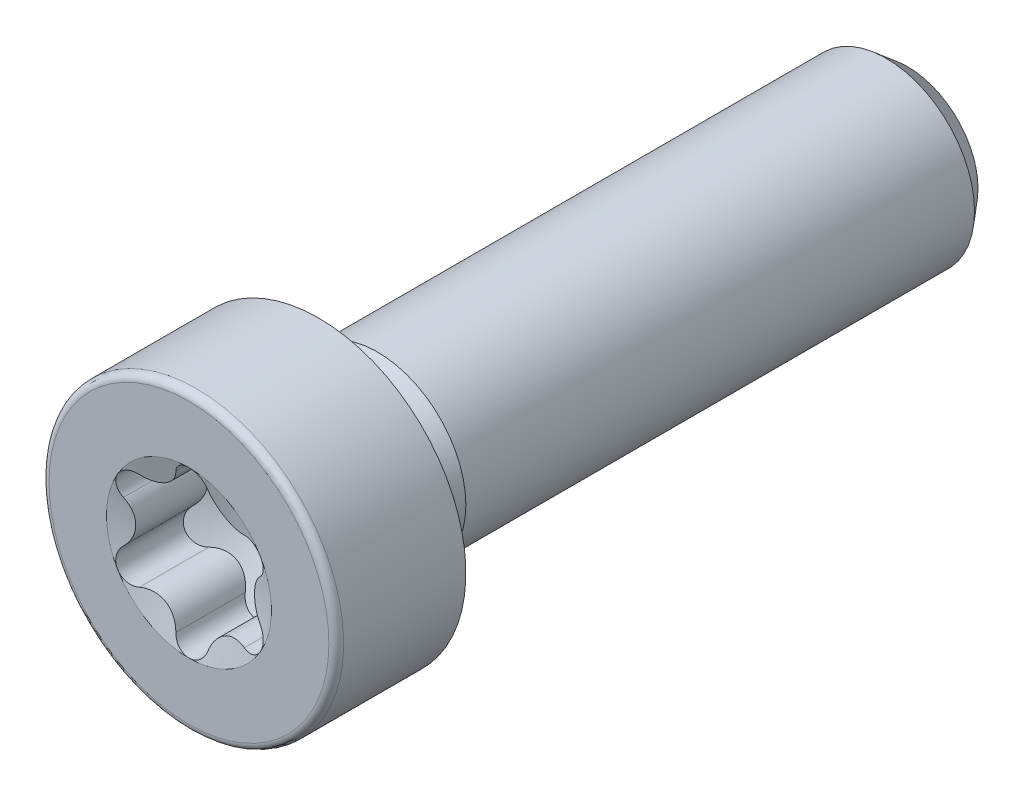
SolidWorks part; units mm, degrees
material "Plain Carbon Steel"
ref_plane "Front Plane" through (0, 0, 0) normal (0, 0, 1) x (1, 0, 0)
ref_plane "Top Plane" through (0, 0, 0) normal (0, 1, 0) x (1, 0, 0)
ref_plane "Right Plane" through (0, 0, 0) normal (1, 0, 0) x (0, 0, -1)
sketch "head-sketch" plane through (0, 0, 0) normal (1, 0, 0) x (0, 0, -1)
  line L0 (0, 0) -> (-4.4, 0) construction
  line L1 (0, 0) -> (0, 5)
  line L2 (0, 5) -> (-4.15, 5)
  line L3 (-4.4, 2.8) -> (-4.4, 0) construction
  line L4 (-4.4, 2.8) -> (-4.1899, 2.016)
  line L5 (-4.1899, 2.016) -> (-4.1899, 0)
  line L6 (-4.1899, 0) -> (0, 0)
  line L7 (-4.4, 2.8) -> (-4.4, 4.75)
  arc A1 (-4.4, 4.75) -> (-4.15, 5) centre (-4.15, 4.75) cw
  dimension "r" = 0.25
  dimension "dk" = 10
  dimension "D2" = 15
  dimension "k" = 4.4
  dimension "A-ref" = 5.6
  dimension "B-ref" = 4.032
ref_plane "6-lobe-plane" through (0, 0, 4.4) normal (0, 0, 1) x (1, 0, 0)
sketch "6-lobe-sketch" plane through (0, 0, 4.4) normal (0, 0, 1) x (1, 0, 0)
  line L0 (0, 0) -> (0, 2.8) construction
  line L1 (0, 0) -> (1.008, 1.7459) construction
  line L2 (1.008, 1.7459) -> (1.498, 2.5946) construction
  line L3 (0, 0) -> (2.4249, 1.4) construction
  line L4 (0, 0) -> (2.4249, -1.4) construction
  line L5 (0, 0) -> (2.996, 0) construction
  line L6 (0, 0) -> (0, -2.8) construction
  line L7 (0, 0) -> (1.498, -2.5946) construction
  line L8 (0, 0) -> (-2.996, 0) construction
  line L9 (0, 0) -> (-1.498, 2.5946) construction
  line L10 (0, 0) -> (-1.498, -2.5946) construction
  line L11 (0, 0) -> (-2.4249, -1.4) construction
  line L12 (0, 0) -> (-2.4249, 1.4) construction
  arc A17 (0.5442, 2.3693) -> (-0.5442, 2.3693) centre (0, 2.2408) ccw
  arc A18 (0.5442, 2.3693) -> (1.7798, 1.656) centre (1.498, 2.5946) ccw
  arc A19 (2.324, 0.7133) -> (1.7798, 1.656) centre (1.9406, 1.1204) ccw
  arc A20 (2.324, 0.7133) -> (2.324, -0.7133) centre (2.996, 0) ccw
  arc A21 (-0.5442, -2.3693) -> (0.5442, -2.3693) centre (0, -2.2408) ccw
  arc A22 (1.7798, -1.656) -> (2.324, -0.7133) centre (1.9406, -1.1204) ccw
  arc A23 (1.7798, -1.656) -> (0.5442, -2.3693) centre (1.498, -2.5946) ccw
  arc A24 (-1.7798, 1.656) -> (-2.324, 0.7133) centre (-1.9406, 1.1204) ccw
  arc A25 (-2.324, -0.7133) -> (-1.7798, -1.656) centre (-1.9406, -1.1204) ccw
  arc A26 (-0.5442, -2.3693) -> (-1.7798, -1.656) centre (-1.498, -2.5946) ccw
  arc A27 (-2.324, -0.7133) -> (-2.324, 0.7133) centre (-2.996, 0) ccw
  arc A28 (-1.7798, 1.656) -> (-0.5442, 2.3693) centre (-1.498, 2.5946) ccw
  arc A29 (-0.5442, 2.3693) -> (-1.7798, 1.656) centre (-1.498, 2.5946) ccw construction
  arc A30 (-1.4563, 0.8408) -> (-1.7798, 1.656) centre (-1.9406, 1.1204) ccw construction
  arc A31 (-2.324, 0.7133) -> (-1.4563, 0.8408) centre (-1.9406, 1.1204) ccw construction
  arc A32 (-2.324, 0.7133) -> (-2.324, -0.7133) centre (-2.996, 0) ccw construction
  arc A33 (-1.4563, -0.8408) -> (-2.324, -0.7133) centre (-1.9406, -1.1204) ccw construction
  arc A34 (-1.7798, -1.656) -> (-1.4563, -0.8408) centre (-1.9406, -1.1204) ccw construction
  arc A35 (-1.7798, -1.656) -> (-0.5442, -2.3693) centre (-1.498, -2.5946) ccw construction
  arc A36 (0, -1.6816) -> (-0.5442, -2.3693) centre (0, -2.2408) ccw construction
  arc A37 (0.5442, -2.3693) -> (0, -1.6816) centre (0, -2.2408) ccw construction
  arc A38 (0.5442, -2.3693) -> (1.7798, -1.656) centre (1.498, -2.5946) ccw construction
  arc A39 (1.4563, -0.8408) -> (1.7798, -1.656) centre (1.9406, -1.1204) ccw construction
  arc A40 (2.324, -0.7133) -> (1.4563, -0.8408) centre (1.9406, -1.1204) ccw construction
  arc A41 (2.324, -0.7133) -> (2.324, 0.7133) centre (2.996, 0) ccw construction
  arc A42 (1.4563, 0.8408) -> (2.324, 0.7133) centre (1.9406, 1.1204) ccw construction
  arc A43 (1.7798, 1.656) -> (1.4563, 0.8408) centre (1.9406, 1.1204) ccw construction
  arc A44 (1.7798, 1.656) -> (0.5442, 2.3693) centre (1.498, 2.5946) ccw construction
  arc A45 (0, 1.6816) -> (0.5442, 2.3693) centre (0, 2.2408) ccw construction
  arc A46 (-0.5442, 2.3693) -> (0, 1.6816) centre (0, 2.2408) ccw construction
  circle A47 centre (0, 0) radius 2.8 construction
  circle A48 centre (0, 0) radius 2.016 construction
  dimension "D1" = 60
  dimension "C-6-lobe" = 1.96
  dimension "A-6-lobe" = 5.6
  dimension "B-6-lobe" = 4.032
sketch "dia-sketch" plane through (0, 0, 0) normal (0, 0, 1) x (1, 0, 0)
  circle A0 centre (0, 0) radius 3
  dimension "dia" = 6
sketch "length-sketch" plane through (0, 0, 0) normal (1, 0, 0) x (0, 0, -1)
  line L0 (0, 0) -> (20, 0) construction
  dimension "length" = 20
ref_plane "length-end-plane" through (0, 0, -20) normal (0, 0, -1) x (-1, 0, 0)
sketch "pitch-sketch" [suppressed] plane through (0, 0, 0) normal (1, 0, 0) x (0, 0, -1)
  line L0 (0, 0) -> (0.4, 0)
  dimension "pitch" = 1
sketch "thread-sketch" plane through (0, 0, 0) normal (1, 0, 0) x (0, 0, -1)
  line L0 (0, 0) -> (20, 0) construction
  line L1 (0, 0) -> (20, 0) construction
  line L2 (0, 3) -> (2, 3)
  line L3 (2, 3) -> (1, 2.675)
  line L4 (1, 2.675) -> (0, 2.675)
  line L5 (0, 2.675) -> (0, 3)
  line L6 (0, 2.675) -> (0, 0) construction
  dimension "Dia-2" = 6
  dimension "threadtransition" = 1
  dimension "pitch-dia" = 5.35
  dimension "runout" = 2
sketch "chamfer-sketch" plane through (0, 0, 0) normal (1, 0, 0) x (0, 0, -1)
  line L0 (20, 0) -> (20, 2.3865) construction
  line L2 (0, 0) -> (20, 0) construction
  line L3 (0, 0) -> (20, 0) construction
  line L4 (20, 2.3865) -> (20, 3)
  line L5 (20, 3) -> (19.2689, 3)
  line L6 (19.2689, 3) -> (20, 2.3865)
  dimension "minor-dia" = 4.773
  dimension "D1" = 50
  dimension "dia-3" = 6
sketch "fillet-sketch" plane through (0, 0, 0) normal (1, 0, 0) x (0, 0, -1)
  line L0 (0, 0) -> (20, 0) construction
  line L1 (0, 0) -> (20, 0) construction
  line L2 (0, 2.675) -> (1, 2.675)
  line L3 (0, 2.675) -> (0, 3.4)
  line L4 (0, 2.675) -> (0, 0) construction
  line L5 (0.1464, 3.0375) -> (0, 3.0375) construction
  arc A0 (1, 2.675) -> (0.1464, 3.0375) centre (1, 3.8613) cw
  arc A1 (0, 3.4) -> (0.1464, 3.0375) centre (0.522, 3.4) ccw
  dimension "r" = 0.522
  dimension "pitch-fillet" = 1
  dimension "fillet-dia" = 5.35
  dimension "da" = 6.8
sketch "socket-depth-sketch" plane through (0, 0, 0) normal (1, 0, 0) x (0, 0, -1)
  line L0 (-4.4, 0) -> (-2.11, 0) construction
  line L1 (-4.1899, 0) -> (0, 0) construction
  line L2 (-2.11, 0) -> (-0.86, 0) construction
  dimension "t" = 2.29
  dimension "t+" = 1.25
ref_plane "socket-bottom-plane" through (0, 0, 0.86) normal (0, 0, -1) x (-1, 0, 0)
sketch "socket-revolve-sketch" plane through (0, 0, 0) normal (1, 0, 0) x (0, 0, -1)
  line L0 (0, 0) -> (0, 5)
  line L1 (0, 5) -> (-2.11, 5)
  line L2 (0, 5) -> (-4.15, 5) construction
  line L3 (-2.11, 5) -> (-2.11, 2.8)
  line L4 (-2.11, 2.8) -> (-0.86, 0)
  line L5 (-0.86, 0) -> (0, 0)
  line L6 (0, 0) -> (1.1467, 0) construction
  line L7 (-2.11, 2.8) -> (-2.11, 0) construction
  line L8 (-2.11, 2.8) -> (-4.4, 2.8) construction
sketch "mat-dia-sketch" plane through (0, 0, -20) normal (0, 0, -1) x (-1, 0, 0)
  circle A0 centre (0, 0) radius 2.4
  dimension "Dx" = 4.8
sketch "mat-length-sketch" plane through (0, 0, 0) normal (1, 0, 0) x (0, 0, -1)
  line L0 (20, 0) -> (23, 0) construction
  dimension "Z4" = 3
ref_plane "mat-end-plane" through (0, 0, -23) normal (0, 0, -1) x (-1, 0, 0)
sketch "mat-cut" plane through (0, 0, 0) normal (1, 0, 0) x (0, 0, -1)
  line L0 (20, 2.4) -> (20, 3)
  line L1 (20, 3) -> (17.55, 3)
  line L2 (17.55, 3) -> (20, 2.4)
  line L3 (22.25, 2.4) -> (23, 2.4)
  line L4 (23, 2.4) -> (23, 2)
  line L5 (20, 0) -> (20, 2.4) construction
  line L7 (20, 0) -> (23, 0) construction
  line L8 (20, -2.4) -> (20, 2.4) construction
  line L9 (20, 2.4) -> (22.25, 2.4) construction
  line L10 (23, -0.8397) -> (23, 0.8397) construction
  line L11 (23, 2) -> (23, 0) construction
  arc A0 (22.25, 2.4) -> (23, 2) centre (22.25, 1.4969) cw
  dimension "mat-dia" = 6
  dimension "U-ref" = 2.45
  dimension "Z5" = 0.75
  dimension "Dy" = 4
sketch "VSMP-boss" plane through (0, 0, 0) normal (1, 0, 0) x (0, 0, -1)
  line L0 (20, 0) -> (12.1951, 0) construction
  line L1 (20, 0) -> (20.9, 0)
  line L2 (20.9, 0) -> (20.9, 2.15)
  line L3 (20.9, 2.15) -> (20, 2.3865)
  line L4 (20, 2.3865) -> (20, 0)
  dimension "Z4" = 0.9
  dimension "Dt" = 4.3
sketch "VSMP-cut" plane through (0, 0, 0) normal (1, 0, 0) x (0, 0, -1)
  line L0 (20, 0) -> (12.1951, 0) construction
  line L1 (20, 2.3865) -> (20, 3)
  line L2 (20, 3) -> (17.45, 3)
  line L3 (17.45, 3) -> (20, 2.3865)
  dimension "Uref" = 2.55
sketch "SDpoint" plane through (0, 0, 0) normal (1, 0, 0) x (0, 0, -1)
  line L0 (20, 0) -> (9.1343, 0) construction
  line L2 (20, 0) -> (21.5, 0)
  line L3 (21.5, 0) -> (21.5, 2)
  line L4 (21.5, 2) -> (20.3865, 2)
  line L5 (20.3865, 2) -> (20, 2.3865)
  line L6 (20, 2.3865) -> (20, 0)
  dimension "D1" = 45
  dimension "z1" = 1.5
  dimension "dp" = 4
sketch "LDpoint" plane through (0, 0, 0) normal (1, 0, 0) x (0, 0, -1)
  line L0 (20, 0) -> (9.1777, 0) construction
  line L2 (20, 0) -> (23, 0)
  line L3 (23, 0) -> (23, 2)
  line L4 (23, 2) -> (20.3865, 2)
  line L5 (20.3865, 2) -> (20, 2.3865)
  line L6 (20, 2.3865) -> (20, 0)
  dimension "D1" = 45
  dimension "dp" = 4
  dimension "z2" = 3
sketch "PCpoint" plane through (0, 0, 0) normal (1, 0, 0) x (0, 0, -1)
  line L0 (20, 0) -> (12.2128, 0) construction
  line L1 (20, 0) -> (23, 0)
  line L2 (23, 0) -> (23, 0.25)
  line L3 (23, 0.25) -> (21, 2.25)
  line L4 (21, 2.25) -> (20.3066, 2.25)
  line L5 (20, 0) -> (20, 2.3865) construction
  line L6 (20, 2.3865) -> (20.3066, 2.25)
  line L7 (20, 2.3865) -> (18.6843, 3)
  line L8 (18.6843, 3) -> (18.6843, 0)
  line L10 (18.6843, 0) -> (20, 0)
  line L11 (18.6843, 3) -> (20, 3) construction
  dimension "D1" = 25
  dimension "D2" = 24
  dimension "D3" = 45
  dimension "z4" = 3
  dimension "z5" = 2
  dimension "D4" = 1.3157
  dimension "dx" = 4.5
sketch "PCpoint-cut" plane through (0, 0, 0) normal (1, 0, 0) x (0, 0, -1)
  line L5 (20, 2.3865) -> (18.6843, 3) construction
  line L6 (20, 2.3865) -> (18.6843, 3)
  line L7 (18.6843, 3) -> (20, 3)
  line L8 (20, 3) -> (20, 2.3865)
  line L9 (20, 0) -> (18.6843, 0) construction
  dimension "cutlength" = 1.3157
sketch "flat-washer" plane through (0, 0, 0) normal (1, 0, 0) x (0, 0, -1)
  line L0 (0, 0) -> (0, 2.81) construction
  line L1 (0, 0) -> (0, 5) construction
  line L2 (0, 0) -> (0.25, 0) construction
  line L3 (0, 2.81) -> (0.25, 2.81)
  line L4 (0, 2.81) -> (0, 2.5)
  line L5 (0, 2.5) -> (0.25, 2.5)
  line L6 (0.25, 2.81) -> (0.25, 2.5)
  line L7 (0, 0) -> (20, 0) construction
  line L8 (0.25, 0) -> (0.25, 2.81) construction
  dimension "D1" = 0.25
  dimension "D2" = 5
  dimension "ID" = 5.62
sketch "conical-washer" plane through (0, 0, 0) normal (1, 0, 0) x (0, 0, -1)
  line L0 (0, 0) -> (0, 2.81) construction
  line L1 (0, 0) -> (0, 5) construction
  line L2 (0, 2.81) -> (0.5, 2.81) construction
  line L3 (0.5, 2.81) -> (0.5, 2) construction
  line L4 (0.5, 2) -> (0, 2) construction
  line L5 (0, 2) -> (0, 2.81) construction
  line L6 (0.5, 2.81) -> (0.5, 0) construction
  line L7 (0, 0) -> (20, 0) construction
  line L8 (0.5, 0) -> (0, 0) construction
  line L9 (0, 2.81) -> (0.25, 2.81) construction
  line L10 (0, 2.724) -> (0.2347, 2.81)
  line L11 (0.2347, 2.81) -> (0.5, 2.086)
  line L12 (0.5, 2.086) -> (0.2653, 2)
  line L13 (0.2653, 2) -> (0, 2.724)
  dimension "D1" = 0.5
  dimension "D2" = 4
  dimension "D3" = 0.25
sketch "double-washer" plane through (0, 0, 0) normal (1, 0, 0) x (0, 0, -1)
  line L0 (0.2653, 2) -> (0, 2.724) construction
  line L1 (0, 2.724) -> (0.2347, 2.81) construction
  line L2 (0.2347, 2.81) -> (0.5, 2.086) construction
  line L3 (0.5, 2.086) -> (0.2653, 2) construction
  line L4 (0.2653, 2) -> (0, 2.724)
  line L5 (0, 2.724) -> (0.2347, 2.81)
  line L6 (0.2347, 2.81) -> (0.5, 2.086)
  line L7 (0.5, 2.086) -> (0.2653, 2)
  line L8 (0, 2.5) -> (0.25, 2.5) construction
  line L9 (0.5, 2.81) -> (0.75, 2.81)
  line L10 (0.5, 2.81) -> (0.5, 2.5)
  line L11 (0.5, 2.5) -> (0.75, 2.5)
  line L12 (0.75, 2.81) -> (0.75, 2.5)
  line L13 (0, 0) -> (0.75, 0) construction
  line L14 (0, 0) -> (20, 0) construction
  line L15 (0.75, 0) -> (0.75, 2.81) construction
sketch "B" plane through (0, 0, 0) normal (1, 0, 0) x (0, 0, -1)
  line L0 (20, 0) -> (-18, 0) construction
  line L1 (0, 0) -> (20, 0) construction
  dimension "B" = 38
sketch "hA" plane through (0, 0, 0) normal (1, 0, 0) x (0, 0, -1)
  line L0 (0, 0) -> (0.75, 0) construction
  line L1 (0, 0) -> (20, 0) construction
  dimension "hA" = 0.75
sketch "flat-thread-cut" plane through (0, 0, 0) normal (1, 0, 0) x (0, 0, -1)
  line L0 (0, 3) -> (0, 0) construction
  line L1 (0, 0) -> (0, 5) construction
  line L2 (0, 0) -> (0.25, 0) construction
  line L3 (0, 0) -> (20, 0) construction
  line L4 (0.25, 0) -> (0.25, 2.675) construction
  line L5 (0.25, 2.675) -> (1.25, 3)
  line L6 (1.25, 3) -> (0, 3)
  line L7 (0, 3) -> (0, 2.675)
  line L8 (0, 2.675) -> (0.25, 2.675)
  dimension "D1" = 1
  dimension "D2" = 6
  dimension "A" = 0.25
  dimension "D4" = 5.35
sketch "conical-thread-cut" plane through (0, 0, 0) normal (1, 0, 0) x (0, 0, -1)
  line L0 (0, 3) -> (0, 0) construction
  line L2 (0, 0) -> (0.5, 0) construction
  line L4 (0.5, 0) -> (0.5, 2.675) construction
  line L5 (0.5, 2.675) -> (1.5, 3)
  line L6 (1.5, 3) -> (0, 3)
  line L7 (0, 3) -> (0, 2.675)
  line L8 (0, 2.675) -> (0.5, 2.675)
  dimension "D1" = 1
  dimension "D2" = 6
  dimension "D4" = 5.35
  dimension "A" = 0.5
sketch "double-thread-cut" plane through (0, 0, 0) normal (1, 0, 0) x (0, 0, -1)
  line L0 (0, 3) -> (0, 0) construction
  line L2 (0, 0) -> (0.75, 0) construction
  line L4 (0.75, 0) -> (0.75, 2.675) construction
  line L5 (0.75, 2.675) -> (1.75, 3)
  line L6 (1.75, 3) -> (0, 3)
  line L7 (0, 3) -> (0, 2.675)
  line L8 (0, 2.675) -> (0.75, 2.675)
  dimension "D1" = 1
  dimension "D2" = 6
  dimension "D4" = 5.35
  dimension "A" = 0.75
sketch "head-cut" plane through (0, 0, 4.4) normal (0, 0, 1) x (1, 0, 0)
  circle A0 centre (0, 0) radius 5.5
  dimension "OD" = 11
ref_plane "head-cut-end" through (0, 0, 0) normal (0, 0, -1) x (-1, 0, 0)
sketch "low-head" plane through (0, 0, 0) normal (1, 0, 0) x (0, 0, -1)
  line L0 (0, 0) -> (3.5646, 0) construction
  line L1 (0, 0) -> (-1.5, 0)
  line L2 (-1.5, 0) -> (-1.5, 4.5)
  line L3 (-1.5, 4.5) -> (-1, 5)
  line L4 (-1, 5) -> (-0.25, 5)
  line L5 (0, 4.75) -> (0, 0)
  arc A0 (-0.25, 5) -> (0, 4.75) centre (-0.25, 4.75) cw
  dimension "r-low" = 0.25
  dimension "k-low" = 1.5
  dimension "d2" = 10
  dimension "v" = 0.5
  dimension "D3" = 45
sketch "low-socket-depth" plane through (0, 0, 0) normal (1, 0, 0) x (0, 0, -1)
  line L0 (-1.5, 0) -> (0.6, 0) construction
  line L1 (0, 0) -> (-1.5, 0) construction
  line L2 (0.6, 0) -> (1.05, 0) construction
  line L3 (0, 0) -> (3.5646, 0) construction
  dimension "t" = 2.1
  dimension "t+" = 0.45
ref_plane "low-6-lobe" through (0, 0, 1.5) normal (0, 0, 1) x (1, 0, 0)
ref_plane "low-socket-end" through (0, 0, -1.05) normal (0, 0, -1) x (-1, 0, 0)
sketch "small-6-lobe" plane through (0, 0, 1.5) normal (0, 0, 1) x (1, 0, 0)
  line L0 (0, 1.5805) -> (0, -1.5805) construction
  line L1 (1.0566, 1.8301) -> (0, 0) construction
  circle A15 centre (0, 0) radius 1.422 construction
  circle A16 centre (0, 0) radius 1.975 construction
  arc A17 (0.3839, 1.6712) -> (-0.3839, 1.6712) centre (0, 1.5805) ccw
  arc A18 (0.3839, 1.6712) -> (1.2554, 1.1681) centre (1.0566, 1.8301) ccw
  arc A19 (-0.3839, -1.6712) -> (0.3839, -1.6712) centre (0, -1.5805) ccw
  arc A20 (1.6393, 0.5032) -> (1.2554, 1.1681) centre (1.3688, 0.7903) ccw
  arc A21 (1.2554, -1.1681) -> (1.6393, -0.5032) centre (1.3688, -0.7903) ccw
  arc A22 (-1.6393, -0.5032) -> (-1.2554, -1.1681) centre (-1.3688, -0.7903) ccw
  arc A23 (-1.2554, 1.1681) -> (-1.6393, 0.5032) centre (-1.3688, 0.7903) ccw
  arc A24 (1.6393, 0.5032) -> (1.6393, -0.5032) centre (2.1132, 0) ccw
  arc A25 (1.2554, -1.1681) -> (0.3839, -1.6712) centre (1.0566, -1.8301) ccw
  arc A26 (-0.3839, -1.6712) -> (-1.2554, -1.1681) centre (-1.0566, -1.8301) ccw
  arc A27 (-1.6393, -0.5032) -> (-1.6393, 0.5032) centre (-2.1132, 0) ccw
  arc A28 (-1.2554, 1.1681) -> (-0.3839, 1.6712) centre (-1.0566, 1.8301) ccw
  arc A29 (1.4924, 1.2936) -> (0.374, 1.9393) centre (1.0566, 1.8301) ccw construction
  arc A30 (1.8665, -0.6457) -> (1.8665, 0.6457) centre (2.1132, 0) ccw construction
  arc A31 (0.374, -1.9393) -> (1.4924, -1.2936) centre (1.0566, -1.8301) ccw construction
  arc A32 (-1.4924, -1.2936) -> (-0.374, -1.9393) centre (-1.0566, -1.8301) ccw construction
  arc A33 (-1.8665, 0.6457) -> (-1.8665, -0.6457) centre (-2.1132, 0) ccw construction
  arc A34 (-0.374, 1.9393) -> (-1.4924, 1.2936) centre (-1.0566, 1.8301) ccw construction
  arc A35 (-0.3401, 1.3807) -> (0, 1.1861) centre (0, 1.5805) ccw construction
  arc A36 (0, 1.1861) -> (0.3401, 1.3807) centre (0, 1.5805) ccw construction
  arc A37 (1.0257, 0.9849) -> (1.3658, 0.3958) centre (1.3688, 0.7903) ccw construction
  arc A38 (1.3658, -0.3958) -> (1.0257, -0.9849) centre (1.3688, -0.7903) ccw construction
  arc A39 (0.3401, -1.3807) -> (0, -1.1861) centre (0, -1.5805) ccw construction
  arc A40 (0, -1.1861) -> (-0.3401, -1.3807) centre (0, -1.5805) ccw construction
  arc A41 (-1.0257, -0.9849) -> (-1.3658, -0.3958) centre (-1.3688, -0.7903) ccw construction
  arc A42 (-1.3658, 0.3958) -> (-1.0257, 0.9849) centre (-1.3688, 0.7903) ccw construction
  arc A43 (0.374, 1.9393) -> (0.3839, 1.6712) centre (1.0566, 1.8301) ccw construction
  arc A44 (1.2554, 1.1681) -> (1.4924, 1.2936) centre (1.0566, 1.8301) ccw construction
  arc A45 (1.8665, 0.6457) -> (1.6393, 0.5032) centre (2.1132, 0) ccw construction
  arc A46 (1.6393, -0.5032) -> (1.8665, -0.6457) centre (2.1132, 0) ccw construction
  arc A47 (1.4924, -1.2936) -> (1.2554, -1.1681) centre (1.0566, -1.8301) ccw construction
  arc A48 (0.3839, -1.6712) -> (0.374, -1.9393) centre (1.0566, -1.8301) ccw construction
  arc A49 (-0.374, -1.9393) -> (-0.3839, -1.6712) centre (-1.0566, -1.8301) ccw construction
  arc A50 (-1.2554, -1.1681) -> (-1.4924, -1.2936) centre (-1.0566, -1.8301) ccw construction
  arc A51 (-1.8665, -0.6457) -> (-1.6393, -0.5032) centre (-2.1132, 0) ccw construction
  arc A52 (-1.6393, 0.5032) -> (-1.8665, 0.6457) centre (-2.1132, 0) ccw construction
  arc A53 (-1.4924, 1.2936) -> (-1.2554, 1.1681) centre (-1.0566, 1.8301) ccw construction
  arc A54 (-0.3839, 1.6712) -> (-0.374, 1.9393) centre (-1.0566, 1.8301) ccw construction
  arc A55 (0.3401, 1.3807) -> (0.3839, 1.6712) centre (0, 1.5805) ccw construction
  arc A56 (1.2554, 1.1681) -> (1.0257, 0.9849) centre (1.3688, 0.7903) ccw construction
  arc A57 (1.3658, 0.3958) -> (1.6393, 0.5032) centre (1.3688, 0.7903) ccw construction
  arc A58 (1.6393, -0.5032) -> (1.3658, -0.3958) centre (1.3688, -0.7903) ccw construction
  arc A59 (1.0257, -0.9849) -> (1.2554, -1.1681) centre (1.3688, -0.7903) ccw construction
  arc A60 (0.3839, -1.6712) -> (0.3401, -1.3807) centre (0, -1.5805) ccw construction
  arc A61 (-0.3401, -1.3807) -> (-0.3839, -1.6712) centre (0, -1.5805) ccw construction
  arc A62 (-1.2554, -1.1681) -> (-1.0257, -0.9849) centre (-1.3688, -0.7903) ccw construction
  arc A63 (-1.3658, -0.3958) -> (-1.6393, -0.5032) centre (-1.3688, -0.7903) ccw construction
  arc A64 (-1.6393, 0.5032) -> (-1.3658, 0.3958) centre (-1.3688, 0.7903) ccw construction
  arc A65 (-1.0257, 0.9849) -> (-1.2554, 1.1681) centre (-1.3688, 0.7903) ccw construction
  arc A66 (-0.3839, 1.6712) -> (-0.3401, 1.3807) centre (0, 1.5805) ccw construction
  point P2 (0, 0)
  dimension "A" = 3.95
  dimension "B" = 2.844
  dimension "C" = 1.3825
  dimension "D3" = 30
sketch "low-socket-revolve" plane through (0, 0, 0) normal (1, 0, 0) x (0, 0, -1)
  line L0 (0.6, 1.975) -> (1.05, 0)
  line L1 (1.05, 0) -> (1.1, 0)
  line L2 (1.1, 0) -> (1.1, 2.075)
  line L3 (1.1, 2.075) -> (0.6, 2.075)
  line L4 (0.6, 2.075) -> (0.6, 1.975)
  line L5 (0.6, 1.975) -> (-1.5, 1.975) construction
  line L6 (1.05, -0.165) -> (1.05, 0.165) construction
  line L7 (0.6, 1.975) -> (0.6, 0) construction
  line L8 (1.05, 0) -> (0.6, 0) construction
  line L9 (-1.5, 0) -> (-1.5, 4.5) construction
  dimension "D1" = 0.1
  dimension "D2" = 0.05
  dimension "A" = 3.95
sketch "threads" plane through (0, 0, 0) normal (1, 0, 0) x (0, 0, -1)
  line L0 (0, 0) -> (20, 0) construction
  line L1 (0, 0) -> (20, 0) construction
  line L2 (20, 2.3865) -> (2, 2.3865)
  line L3 (20, 2.3865) -> (20, 3)
  line L4 (20, 3) -> (19.2689, 3)
  line L5 (19.2689, 3) -> (20, 2.3865)
  line L8 (19.2689, 3) -> (20, 2.3865) construction
  line L9 (2, 2.3865) -> (1, 2.675)
  line L10 (2, 3) -> (0, 3)
  line L11 (1, 2.675) -> (2, 3)
  line L12 (0, 2.675) -> (1, 2.675)
  line L13 (0, 3) -> (0, 2.675)
  line L15 (1, 2.675) -> (2, 3) construction
  line L18 (20, -2.3865) -> (2, -2.3865)
  line L19 (2, -2.3865) -> (1, -2.675)
  dimension "D1" = 0
  dimension "D2" = 0
sketch "patches-1" plane through (0, 0, 0) normal (0, 1, 0) x (1, 0, 0)
  line L0 (0, 20) -> (0, 18)
  dimension "plane length" = 2
ref_plane "patches-2" through (0, 0, -18) normal (0, 0, -1) x (-1, 0, 0)
sketch "180-patch-1" plane through (0, 0, 0) normal (1, 0, 0) x (0, 0, -1)
  line L0 (0, 0) -> (20, 0) construction
  line L1 (11, 3) -> (11, 0) construction
  line L2 (11, 0) -> (14, 0) construction
  circle A0 centre (14, 3) radius 3
  dimension "D2" = 4
  dimension "D1" = 6
sketch "180-patch-2" plane through (0, 0, 0) normal (0, 1, 0) x (1, 0, 0)
  line L0 (0, 14) -> (4.5, 14) construction
  line L1 (0, 0) -> (0, 14) construction
  line L2 (0, 14) -> (-4.5, 14) construction
  dimension "D1" = 9
ref_plane "180-patch-3" through (4.5, 0, -14) normal (1, 0, 0) x (0, 0, -1)
sketch "180-patch-4" plane through (0, 0, -20) normal (0, 0, -1) x (-1, 0, 0)
  circle A0 centre (0, 0) radius 3.01
  circle A1 centre (0, 0) radius 9
  dimension "D1" = 6.02
  dimension "D2" = 18
ref_plane "180-patch-5" through (0, 0, -11) normal (0, 0, -1) x (-1, 0, 0)
ref_plane "180-patch-6" through (-4.5, 0, -14) normal (-1, 0, 0) x (0, 0, 1)
sketch "360-patch" plane through (0, 0, 0) normal (1, 0, 0) x (0, 0, -1)
  line L0 (0, 0) -> (20, 0) construction
  line L1 (11, 3) -> (17, 3)
  line L2 (11, 3) -> (11, 3.01)
  line L3 (11, 3.01) -> (17, 3.01)
  line L4 (17, 3) -> (17, 3.01)
  line L6 (18, 0) -> (18, 3) construction
  line L7 (18, -1.0038) -> (18, 1.0038) construction
  line L8 (17, 3) -> (18, 3) construction
  dimension "D1" = 6
  dimension "D3" = 6
  dimension "D4" = 0.01
  dimension "D2" = 1
sketch "Sketch8" plane through (0, 0, 0) normal (1, 0, 0) x (0, 0, -1)
  line L0 (0, 0) -> (-4.4, 0) construction
  line L1 (-4.4, 2.8) -> (-4.1899, 2.016) construction
  line L2 (-4.1899, 2.016) -> (-4.1899, 0) construction
  line L3 (-4.1899, 0) -> (0, 0) construction
  line L4 (0, 0) -> (0, 5) construction
  line L5 (0, 5) -> (-4.15, 5) construction
  line L6 (0, 0) -> (-4.4, 0) construction
  line L7 (-4.4, 2.8) -> (-4.1899, 2.016)
  line L8 (-4.1899, 2.016) -> (-4.1899, 0)
  line L9 (-4.1899, 0) -> (0, 0)
  line L10 (0, 0) -> (0, 5)
  line L11 (0, 5) -> (-4.15, 5)
  line L12 (-4.4, 2.8) -> (-4.4, 4.75) construction
  line L13 (-4.4, 2.8) -> (-4.4, 4.75)
  arc A1 (-4.15, 5) -> (-4.4, 4.75) centre (-4.15, 4.75) ccw construction
  arc A2 (-4.15, 5) -> (-4.4, 4.75) centre (-4.15, 4.75) ccw
revolve "Head-Revolve1" add sketch "Sketch8" angle 360 about L6
sketch "Sketch9" plane through (0, 0, 4.4) normal (0, 0, 1) x (1, 0, 0)
  arc A36 (0.5442, 2.3693) -> (1.7798, 1.656) centre (1.498, 2.5946) ccw
  arc A37 (2.324, 0.7133) -> (1.7798, 1.656) centre (1.9406, 1.1204) ccw
  arc A38 (2.324, 0.7133) -> (2.324, -0.7133) centre (2.996, 0) ccw
  arc A39 (1.7798, -1.656) -> (2.324, -0.7133) centre (1.9406, -1.1204) ccw
  arc A40 (1.7798, -1.656) -> (0.5442, -2.3693) centre (1.498, -2.5946) ccw
  arc A41 (-0.5442, -2.3693) -> (0.5442, -2.3693) centre (0, -2.2408) ccw
  arc A42 (-0.5442, -2.3693) -> (-1.7798, -1.656) centre (-1.498, -2.5946) ccw
  arc A43 (-2.324, -0.7133) -> (-1.7798, -1.656) centre (-1.9406, -1.1204) ccw
  arc A44 (-2.324, -0.7133) -> (-2.324, 0.7133) centre (-2.996, 0) ccw
  arc A45 (-1.7798, 1.656) -> (-2.324, 0.7133) centre (-1.9406, 1.1204) ccw
  arc A46 (-1.7798, 1.656) -> (-0.5442, 2.3693) centre (-1.498, 2.5946) ccw
  arc A47 (0.5442, 2.3693) -> (-0.5442, 2.3693) centre (0, 2.2408) ccw
  arc A48 (0.5442, 2.3693) -> (1.7798, 1.656) centre (1.498, 2.5946) ccw
  arc A49 (2.324, 0.7133) -> (1.7798, 1.656) centre (1.9406, 1.1204) ccw
  arc A50 (2.324, 0.7133) -> (2.324, -0.7133) centre (2.996, 0) ccw
  arc A51 (1.7798, -1.656) -> (2.324, -0.7133) centre (1.9406, -1.1204) ccw
  arc A52 (1.7798, -1.656) -> (0.5442, -2.3693) centre (1.498, -2.5946) ccw
  arc A53 (-0.5442, -2.3693) -> (0.5442, -2.3693) centre (0, -2.2408) ccw
  arc A54 (-0.5442, -2.3693) -> (-1.7798, -1.656) centre (-1.498, -2.5946) ccw
  arc A55 (-2.324, -0.7133) -> (-1.7798, -1.656) centre (-1.9406, -1.1204) ccw
  arc A56 (-2.324, -0.7133) -> (-2.324, 0.7133) centre (-2.996, 0) ccw
  arc A57 (-1.7798, 1.656) -> (-2.324, 0.7133) centre (-1.9406, 1.1204) ccw
  arc A58 (-1.7798, 1.656) -> (-0.5442, 2.3693) centre (-1.498, 2.5946) ccw
  arc A59 (0.5442, 2.3693) -> (-0.5442, 2.3693) centre (0, 2.2408) ccw
  dimension "D1" = 0
extrude "socket-Cut-Extrude1" cut sketch "Sketch9" against normal up to surface (3.54 mm away)
sketch "Sketch12" plane through (0, 0, 0) normal (1, 0, 0) x (0, 0, -1)
  line L0 (-2.11, 5) -> (-2.11, 2.8) construction
  line L1 (-2.11, 2.8) -> (-0.86, 0) construction
  line L2 (-0.86, 0) -> (0, 0) construction
  line L3 (0, 0) -> (0, 5) construction
  line L4 (0, 5) -> (-2.11, 5) construction
  line L5 (-2.11, 5) -> (-2.11, 2.8)
  line L6 (-2.11, 2.8) -> (-0.86, 0)
  line L7 (-0.86, 0) -> (0, 0)
  line L8 (0, 0) -> (0, 5)
  line L9 (0, 5) -> (-2.11, 5)
  line L10 (0, 0) -> (1.1467, 0) construction
  line L11 (0, 0) -> (1.1467, 0) construction
revolve "Socket-Revolve2" add sketch "Sketch12" angle 360 about L11
sketch "Sketch13" plane through (0, 0, 0) normal (0, 0, 1) x (1, 0, 0)
  circle A0 centre (0, 0) radius 3 construction
  circle A1 centre (0, 0) radius 3
extrude "Length-Boss-Extrude1" add sketch "Sketch13" against normal up to surface (20 mm away) up to plane "length-end-plane"
sketch "Sketch14" plane through (0, 0, 0) normal (1, 0, 0) x (0, 0, -1)
  line L0 (0, 0) -> (20, 0) construction
  line L1 (0, 3) -> (2, 3) construction
  line L2 (2, 3) -> (1, 2.675) construction
  line L3 (1, 2.675) -> (0, 2.675) construction
  line L4 (0, 2.675) -> (0, 3) construction
  line L5 (0, 0) -> (20, 0) construction
  line L6 (0, 3) -> (2, 3)
  line L7 (2, 3) -> (1, 2.675)
  line L8 (1, 2.675) -> (0, 2.675)
  line L9 (0, 2.675) -> (0, 3)
revolve "Runout-Cut-Revolve1" cut sketch "Sketch14" angle 360 about L5
sketch "Sketch15" plane through (0, 0, 0) normal (1, 0, 0) x (0, 0, -1)
  line L0 (0, 2.675) -> (1, 2.675) construction
  line L1 (0, 2.675) -> (0, 3.4) construction
  line L2 (0, 0) -> (20, 0) construction
  line L3 (0, 2.675) -> (0, 0) construction
  line L4 (0, 2.675) -> (1, 2.675)
  line L5 (0, 2.675) -> (0, 3.4)
  line L6 (0, 0) -> (20, 0) construction
  line L7 (0, 2.675) -> (0, 0)
  arc A0 (0, 3.4) -> (0.1464, 3.0375) centre (0.522, 3.4) ccw construction
  arc A1 (0.1464, 3.0375) -> (1, 2.675) centre (1, 3.8613) ccw construction
  arc A2 (0, 3.4) -> (0.1464, 3.0375) centre (0.522, 3.4) ccw
  arc A3 (0.1464, 3.0375) -> (1, 2.675) centre (1, 3.8613) ccw
revolve "Fillet-Revolve3" add sketch "Sketch15" angle 360 about L6
sketch "Sketch16" plane through (0, 0, 0) normal (1, 0, 0) x (0, 0, -1)
  line L0 (0, 0) -> (20, 0) construction
  line L1 (20, 3) -> (19.2689, 3) construction
  line L2 (19.2689, 3) -> (20, 2.3865) construction
  line L3 (20, 2.3865) -> (20, 3) construction
  line L4 (0, 0) -> (20, 0) construction
  line L5 (20, 3) -> (19.2689, 3)
  line L6 (19.2689, 3) -> (20, 2.3865)
  line L7 (20, 2.3865) -> (20, 3)
revolve "Chamfer-Cut-Revolve2" cut sketch "Sketch16" angle 360 about L4
sketch "Sketch21" plane through (0, 0, -20) normal (0, 0, -1) x (-1, 0, 0)
  circle A0 centre (0, 0) radius 2.4 construction
  circle A1 centre (0, 0) radius 2.4
extrude "matpoint-Boss-Extrude1" [suppressed] add sketch "Sketch21" along normal up to surface (4.8 mm away)
sketch "Sketch22" plane through (0, 0, 0) normal (1, 0, 0) x (0, 0, -1)
  line L0 (20, 0) -> (23, 0) construction
  line L1 (23, 2.4) -> (23, 2) construction
  line L2 (22.25, 2.4) -> (23, 2.4) construction
  line L3 (20, 3) -> (17.55, 3) construction
  line L4 (17.55, 3) -> (20, 2.4) construction
  line L5 (20, 2.4) -> (20, 3) construction
  line L6 (20, 0) -> (23, 0) construction
  line L7 (23, 2.4) -> (23, 2)
  line L8 (22.25, 2.4) -> (23, 2.4)
  line L9 (20, 3) -> (17.55, 3)
  line L10 (17.55, 3) -> (20, 2.4)
  line L11 (20, 2.4) -> (20, 3)
  arc A0 (23, 2) -> (22.25, 2.4) centre (22.25, 1.4969) ccw construction
  arc A1 (23, 2) -> (22.25, 2.4) centre (22.25, 1.4969) ccw
revolve "matpoint-Cut-Revolve1" [suppressed] cut sketch "Sketch22" angle 360 about L6
sketch "Sketch40" plane through (0, 0, 0) normal (1, 0, 0) x (0, 0, -1)
  line L0 (20, 0) -> (12.1951, 0) construction
  line L1 (20.9, 2.15) -> (20, 2.3865) construction
  line L2 (20, 2.3865) -> (20, 0) construction
  line L3 (20, 0) -> (20.9, 0) construction
  line L4 (20.9, 0) -> (20.9, 2.15) construction
  line L5 (20, 0) -> (12.1951, 0) construction
  line L6 (20.9, 2.15) -> (20, 2.3865)
  line L7 (20, 2.3865) -> (20, 0)
  line L8 (20, 0) -> (20.9, 0)
  line L9 (20.9, 0) -> (20.9, 2.15)
revolve "VSMP-revolve" [suppressed] add sketch "Sketch40" angle 360 about L5
sketch "Sketch41" plane through (0, 0, 0) normal (1, 0, 0) x (0, 0, -1)
  line L0 (20, 0) -> (12.1951, 0) construction
  line L1 (20, 3) -> (17.45, 3) construction
  line L2 (17.45, 3) -> (20, 2.3865) construction
  line L3 (20, 2.3865) -> (20, 3) construction
  line L4 (20, 0) -> (12.1951, 0) construction
  line L5 (20, 3) -> (17.45, 3)
  line L6 (17.45, 3) -> (20, 2.3865)
  line L7 (20, 2.3865) -> (20, 3)
revolve "VSMP-Cut-Revolve" [suppressed] cut sketch "Sketch41" angle 360 about L4
sketch "Sketch42" plane through (0, 0, 0) normal (1, 0, 0) x (0, 0, -1)
  line L0 (23, 2) -> (20.3865, 2) construction
  line L1 (20.3865, 2) -> (20, 2.3865) construction
  line L2 (20, 2.3865) -> (20, 0) construction
  line L3 (20, 0) -> (23, 0) construction
  line L4 (23, 0) -> (23, 2) construction
  line L5 (20, 0) -> (9.1777, 0) construction
  line L6 (23, 2) -> (20.3865, 2)
  line L7 (20.3865, 2) -> (20, 2.3865)
  line L8 (20, 2.3865) -> (20, 0)
  line L9 (20, 0) -> (23, 0)
  line L10 (23, 0) -> (23, 2)
  line L11 (20, 0) -> (9.1777, 0) construction
revolve "LD" [suppressed] add sketch "Sketch42" angle 360 about L11
sketch "Sketch43" [suppressed] plane through (0, 0, 0) normal (1, 0, 0) x (0, 0, -1)
  line L0 (10, 0) -> (9.1343, 0) construction
  line L1 (10.5, 0.5) -> (10.2545, 0.5) construction
  line L2 (10.2545, 0.5) -> (10, 0.7545) construction
  line L3 (10, 0.7545) -> (10, 0) construction
  line L4 (10, 0) -> (10.5, 0) construction
  line L5 (10.5, 0) -> (10.5, 0.5) construction
  line L6 (10, 0) -> (9.1343, 0) construction
  line L7 (10.5, 0.5) -> (10.2545, 0.5)
  line L8 (10.2545, 0.5) -> (10, 0.7545)
  line L9 (10, 0.7545) -> (10, 0)
  line L10 (10, 0) -> (10.5, 0)
  line L11 (10.5, 0) -> (10.5, 0.5)
revolve "SD" [suppressed] add sketch "Sketch43" angle 360 about L6
sketch "Sketch44" plane through (0, 0, 0) normal (1, 0, 0) x (0, 0, -1)
  line L0 (21, 2.25) -> (20.3066, 2.25) construction
  line L1 (20, 2.3865) -> (20.3066, 2.25) construction
  line L2 (20, 2.3865) -> (18.6843, 3) construction
  line L3 (18.6843, 3) -> (18.6843, 0) construction
  line L4 (18.6843, 0) -> (20, 0) construction
  line L5 (20, 0) -> (23, 0) construction
  line L6 (23, 0) -> (23, 0.25) construction
  line L7 (23, 0.25) -> (21, 2.25) construction
  line L8 (20, 0) -> (12.2128, 0) construction
  line L9 (20, 0) -> (20, 2.3865) construction
  line L10 (21, 2.25) -> (20.3066, 2.25)
  line L11 (20, 2.3865) -> (20.3066, 2.25)
  line L12 (20, 2.3865) -> (18.6843, 3)
  line L13 (18.6843, 3) -> (18.6843, 0)
  line L14 (18.6843, 0) -> (20, 0)
  line L15 (20, 0) -> (23, 0)
  line L16 (23, 0) -> (23, 0.25)
  line L17 (23, 0.25) -> (21, 2.25)
  line L18 (20, 0) -> (12.2128, 0) construction
  line L19 (20, 0) -> (20, 2.3865)
revolve "PC" [suppressed] add sketch "Sketch44" angle 360 about L18
sketch "Sketch45" plane through (0, 0, 0) normal (1, 0, 0) x (0, 0, -1)
  line L0 (20, 0) -> (18.6843, 0) construction
  line L1 (18.6843, 3) -> (20, 3) construction
  line L2 (20, 3) -> (20, 2.3865) construction
  line L3 (20, 2.3865) -> (18.6843, 3) construction
  line L4 (20, 0) -> (18.6843, 0) construction
  line L5 (18.6843, 3) -> (20, 3)
  line L6 (20, 3) -> (20, 2.3865)
  line L7 (20, 2.3865) -> (18.6843, 3)
revolve "PC-cut" [suppressed] cut sketch "Sketch45" angle 360 about L4
sketch "Sketch46" [suppressed] plane through (0, 0, 0) normal (1, 0, 0) x (0, 0, -1)
  line L0 (0, 0) -> (0.25, 0) construction
  line L1 (0, 0.935) -> (0, 2.5) construction
  line L2 (0, 2.5) -> (0.25, 2.5) construction
  line L3 (0.25, 0.935) -> (0.25, 2.5) construction
  line L4 (0, 0.935) -> (0.25, 0.935) construction
  line L5 (0, 0) -> (0.25, 0) construction
  line L6 (0, 0.935) -> (0, 2.5)
  line L7 (0, 2.5) -> (0.25, 2.5)
  line L8 (0.25, 0.935) -> (0.25, 2.5)
  line L9 (0, 0.935) -> (0.25, 0.935)
revolve "Flat SEMS" [suppressed] add sketch "Sketch46" angle 360 about L5
sketch "Sketch47" [suppressed] plane through (0, 0, 0) normal (1, 0, 0) x (0, 0, -1)
  line L0 (0.2579, 2) -> (0, 0.9973) construction
  line L1 (0, 0.9973) -> (0.2421, 0.935) construction
  line L2 (0.2421, 0.935) -> (0.5, 1.9377) construction
  line L3 (0.5, 1.9377) -> (0.2579, 2) construction
  line L4 (0.5, 0) -> (0, 0) construction
  line L7 (0.2579, 2) -> (0, 0.9973)
  line L8 (0, 0.9973) -> (0.2421, 0.935)
  line L9 (0.2421, 0.935) -> (0.5, 1.9377)
  line L10 (0.5, 1.9377) -> (0.2579, 2)
  line L11 (0.5, 0) -> (0, 0) construction
revolve "Conical SEMS" [suppressed] add sketch "Sketch47" angle 360 about L11
sketch "Sketch48" [suppressed] plane through (0, 0, 0) normal (1, 0, 0) x (0, 0, -1)
  line L0 (0, 0) -> (0.75, 0) construction
  line L1 (0.2421, 0.935) -> (0.5, 1.9377) construction
  line L2 (0.5, 1.9377) -> (0.2579, 2) construction
  line L3 (0.2579, 2) -> (0, 0.9973) construction
  line L4 (0, 0.9973) -> (0.2421, 0.935) construction
  line L5 (0.75, 0.935) -> (0.75, 2.5) construction
  line L6 (0.5, 2.5) -> (0.75, 2.5) construction
  line L7 (0.5, 0.935) -> (0.5, 2.5) construction
  line L8 (0.5, 0.935) -> (0.75, 0.935) construction
  line L9 (0, 0) -> (0.75, 0) construction
  line L10 (0.2421, 0.935) -> (0.5, 1.9377)
  line L11 (0.5, 1.9377) -> (0.2579, 2)
  line L12 (0.2579, 2) -> (0, 0.9973)
  line L13 (0, 0.9973) -> (0.2421, 0.935)
  line L14 (0.75, 0.935) -> (0.75, 2.5)
  line L15 (0.5, 2.5) -> (0.75, 2.5)
  line L16 (0.5, 0.935) -> (0.5, 2.5)
  line L17 (0.5, 0.935) -> (0.75, 0.935)
revolve "Double SEMS" [suppressed] add sketch "Sketch48" angle 360 about L9
sketch "Sketch49" [suppressed] plane through (0, 0, 0) normal (1, 0, 0) x (0, 0, -1)
  line L0 (0.65, 1) -> (0, 1) construction
  line L1 (0, 1) -> (0, 0.87) construction
  line L2 (0, 0.87) -> (0.25, 0.87) construction
  line L3 (0.25, 0.87) -> (0.65, 1) construction
  line L4 (0, 0) -> (0.25, 0) construction
  line L7 (0.65, 1) -> (0, 1)
  line L8 (0, 1) -> (0, 0.87)
  line L9 (0, 0.87) -> (0.25, 0.87)
  line L10 (0.25, 0.87) -> (0.65, 1)
  line L11 (0, 0) -> (0.25, 0) construction
revolve "flat_Cut-Revolve" [suppressed] cut sketch "Sketch49" angle 360 about L11
sketch "Sketch50" [suppressed] plane through (0, 0, 0) normal (1, 0, 0) x (0, 0, -1)
  line L0 (0, 0) -> (0.5, 0) construction
  line L1 (0.9, 1) -> (0, 1) construction
  line L2 (0, 1) -> (0, 0.87) construction
  line L3 (0, 0.87) -> (0.5, 0.87) construction
  line L4 (0.5, 0.87) -> (0.9, 1) construction
  line L5 (0, 0) -> (0.5, 0) construction
  line L6 (0.9, 1) -> (0, 1)
  line L7 (0, 1) -> (0, 0.87)
  line L8 (0, 0.87) -> (0.5, 0.87)
  line L9 (0.5, 0.87) -> (0.9, 1)
revolve "Conical-Cut-Revolve" [suppressed] cut sketch "Sketch50" angle 360 about L5
sketch "Sketch51" [suppressed] plane through (0, 0, 0) normal (1, 0, 0) x (0, 0, -1)
  line L0 (1.15, 1) -> (0, 1) construction
  line L1 (0, 1) -> (0, 0.87) construction
  line L2 (0, 0.87) -> (0.75, 0.87) construction
  line L3 (0.75, 0.87) -> (1.15, 1) construction
  line L4 (0, 0) -> (0.75, 0) construction
  line L7 (1.15, 1) -> (0, 1)
  line L8 (0, 1) -> (0, 0.87)
  line L9 (0, 0.87) -> (0.75, 0.87)
  line L10 (0.75, 0.87) -> (1.15, 1)
  line L11 (0, 0) -> (0.75, 0) construction
revolve "Double-Cut-Revolve" [suppressed] cut sketch "Sketch51" angle 360 about L11
sketch "Sketch59" plane through (0, 0, 4.4) normal (0, 0, 1) x (1, 0, 0)
  circle A0 centre (0, 0) radius 5.5 construction
  circle A1 centre (0, 0) radius 5.5
extrude "head-remove" [suppressed] cut sketch "Sketch59" against normal up to surface (1.55 mm away)
sketch "Sketch60" plane through (0, 0, 0) normal (1, 0, 0) x (0, 0, -1)
  line L0 (0, 0) -> (1.8073, 0) construction
  line L1 (0, 0) -> (20, 0) construction
  line L5 (-1.5, 0) -> (0, 0)
  line L6 (-1.5, 4.5) -> (-1.5, 0)
  line L7 (-1, 5) -> (-1.5, 4.5)
  line L8 (-0.25, 5) -> (-1, 5)
  line L9 (0, 0) -> (0, 4.75)
  line L10 (-1.5, 0) -> (0, 0)
  line L11 (-1.5, 4.5) -> (-1.5, 0)
  line L12 (-1, 5) -> (-1.5, 4.5)
  line L13 (-0.25, 5) -> (-1, 5)
  line L14 (0, 0) -> (0, 4.75)
  arc A1 (0, 4.75) -> (-0.25, 5) centre (-0.25, 4.75) ccw
  arc A2 (0, 4.75) -> (-0.25, 5) centre (-0.25, 4.75) ccw
  dimension "D1" = 0
revolve "low-head-Revolve" [suppressed] add sketch "Sketch60" angle 360 about L0
sketch "Sketch61" plane through (0, 0, 1.5) normal (0, 0, 1) x (1, 0, 0)
  arc A12 (0.3839, 1.6712) -> (-0.3839, 1.6712) centre (0, 1.5805) ccw
  arc A13 (0.3839, 1.6712) -> (-0.3839, 1.6712) centre (0, 1.5805) ccw
  arc A14 (-1.2554, 1.1681) -> (-0.3839, 1.6712) centre (-1.0566, 1.8301) ccw
  arc A15 (-1.2554, 1.1681) -> (-0.3839, 1.6712) centre (-1.0566, 1.8301) ccw
  arc A16 (-1.2554, 1.1681) -> (-1.6393, 0.5032) centre (-1.3688, 0.7903) ccw
  arc A17 (-1.2554, 1.1681) -> (-1.6393, 0.5032) centre (-1.3688, 0.7903) ccw
  arc A18 (-1.6393, -0.5032) -> (-1.6393, 0.5032) centre (-2.1132, 0) ccw
  arc A19 (-1.6393, -0.5032) -> (-1.6393, 0.5032) centre (-2.1132, 0) ccw
  arc A20 (-1.6393, -0.5032) -> (-1.2554, -1.1681) centre (-1.3688, -0.7903) ccw
  arc A21 (-1.6393, -0.5032) -> (-1.2554, -1.1681) centre (-1.3688, -0.7903) ccw
  arc A22 (-0.3839, -1.6712) -> (-1.2554, -1.1681) centre (-1.0566, -1.8301) ccw
  arc A23 (-0.3839, -1.6712) -> (-1.2554, -1.1681) centre (-1.0566, -1.8301) ccw
  arc A36 (-0.3839, -1.6712) -> (0.3839, -1.6712) centre (0, -1.5805) ccw
  arc A37 (-0.3839, -1.6712) -> (0.3839, -1.6712) centre (0, -1.5805) ccw
  arc A38 (1.2554, -1.1681) -> (0.3839, -1.6712) centre (1.0566, -1.8301) ccw
  arc A39 (1.2554, -1.1681) -> (0.3839, -1.6712) centre (1.0566, -1.8301) ccw
  arc A40 (1.2554, -1.1681) -> (1.6393, -0.5032) centre (1.3688, -0.7903) ccw
  arc A41 (1.2554, -1.1681) -> (1.6393, -0.5032) centre (1.3688, -0.7903) ccw
  arc A42 (1.6393, 0.5032) -> (1.6393, -0.5032) centre (2.1132, 0) ccw
  arc A43 (1.6393, 0.5032) -> (1.6393, -0.5032) centre (2.1132, 0) ccw
  arc A44 (1.6393, 0.5032) -> (1.2554, 1.1681) centre (1.3688, 0.7903) ccw
  arc A45 (1.6393, 0.5032) -> (1.2554, 1.1681) centre (1.3688, 0.7903) ccw
  arc A46 (0.3839, 1.6712) -> (1.2554, 1.1681) centre (1.0566, 1.8301) ccw
  arc A47 (0.3839, 1.6712) -> (1.2554, 1.1681) centre (1.0566, 1.8301) ccw
  dimension "D1" = 0
extrude "Small-6-lobe-Cut" [suppressed] cut sketch "Sketch61" against normal up to surface (1.15 mm away)
sketch "Sketch62" plane through (0, 0, 0) normal (1, 0, 0) x (0, 0, -1)
  line L0 (1.05, 0) -> (0.6, 0) construction
  line L5 (0.6, 1.975) -> (1.05, 0)
  line L6 (1.05, 0) -> (1.1, 0)
  line L7 (1.1, 0) -> (1.1, 2.075)
  line L8 (1.1, 2.075) -> (0.6, 2.075)
  line L9 (0.6, 2.075) -> (0.6, 1.975)
  line L10 (0.6, 1.975) -> (1.05, 0)
  line L11 (1.05, 0) -> (1.1, 0)
  line L12 (1.1, 0) -> (1.1, 2.075)
  line L13 (1.1, 2.075) -> (0.6, 2.075)
  line L14 (0.6, 2.075) -> (0.6, 1.975)
  dimension "D1" = 0
revolve "Socket-bottom-Revolve" [suppressed] add sketch "Sketch62" angle 360 about L0
sketch "Sketch66" plane through (0, 0, 0) normal (1, 0, 0) x (0, 0, -1)
  circle A0 centre (14, 3) radius 3 construction
  circle A1 centre (14, 3) radius 3
extrude "180-patch-extrude" [suppressed] add sketch "Sketch66" along normal up to surface and the other way up to surface
sketch "Sketch67" plane through (0, 0, -20) normal (0, 0, -1) x (-1, 0, 0)
  circle A0 centre (0, 0) radius 3.01 construction
  circle A1 centre (0, 0) radius 9 construction
  circle A2 centre (0, 0) radius 3.01
  circle A3 centre (0, 0) radius 9
extrude "180-patch-Cut-Extrude" [suppressed] cut sketch "Sketch67" against normal up to surface (14.5 mm away)
sketch "Sketch70" plane through (0, 0, 0) normal (1, 0, 0) x (0, 0, -1)
  line L0 (0, 0) -> (20, 0) construction
  line L1 (11, 3) -> (17, 3) construction
  line L2 (17, 3) -> (17, 3.01) construction
  line L3 (11, 3.01) -> (17, 3.01) construction
  line L4 (11, 3) -> (11, 3.01) construction
  line L5 (0, 0) -> (20, 0) construction
  line L6 (11, 3) -> (17, 3)
  line L7 (17, 3) -> (17, 3.01)
  line L8 (11, 3.01) -> (17, 3.01)
  line L9 (11, 3) -> (11, 3.01)
revolve "360-patch-Revolve" [suppressed] add sketch "Sketch70" angle 360 about L5
sketch "Symbolic Threads" plane through (0, 0, 0) normal (1, 0, 0) x (0, 0, -1)
  line L0 (20, -2.3865) -> (2, -2.3865) construction
  line L1 (2, -2.3865) -> (1, -2.675) construction
  line L2 (20, 2.3865) -> (2, 2.3865) construction
  line L3 (2, 2.3865) -> (1, 2.675) construction
  line L4 (20, -2.3865) -> (2, -2.3865)
  line L5 (2, -2.3865) -> (1, -2.675)
  line L6 (20, 2.3865) -> (2, 2.3865)
  line L7 (2, 2.3865) -> (1, 2.675)
equation "\"runout@thread-sketch\" = iif ( \"thread_style\" = 1 , 2 , iif ( \"length@length-sketch\" > 40 , ( \"length@length-sketch\" - 38 ) , 2 ) )"
equation "\"minor-dia@chamfer-sketch\" = iif ( \"matpointm\" = 1 , 4.8 , 4.773 )"
equation "\"length@length-sketch\"=\"l_feature\""
equation "\"matpoint-Boss-Extrude1\"= iif ( \"matpointm\" = 1 , \"unsuppressed\" , \"suppressed\" )"
equation "\"matpoint-Cut-Revolve1\"= iif ( \"matpointm\" = 1 , \"unsuppressed\" , \"suppressed\" )"
equation "\"Z4@mat-length-sketch\" = iif ( \"length@length-sketch\" > 50 , 3.1 , 3 )"
equation "\"U-ref@mat-cut\" = iif ( \"length@length-sketch\" > 50 , 2.55 , 2.45 )"
equation "\"threadtransition@thread-sketch\" = iif ( \"thread_style\" = 1 , 1 , iif ( \"length@length-sketch\" > 41.5 , 1 , 1 ) )"
equation "\"D1@flat-washer\" = \"flat_t\""
equation "\"D2@flat-washer\" = \"flat_OD\""
equation "\"D1@conical-washer\" = \"conical_h\""
equation "\"D2@conical-washer\" = \"conical_OD\""
equation "\"D3@conical-washer\" = \"conical_s\""
equation "\"hA@hA\" = \"conical_h\" + \"flat_t\""
equation "\"D1@flat-thread-cut\" = \"threadtransition@thread-sketch\""
equation "\"D2@flat-thread-cut\" = \"Dia-2@thread-sketch\""
equation "\"D4@flat-thread-cut\" = \"pitch-dia@thread-sketch\""
equation "\"D4@conical-thread-cut\" = \"pitch-dia@thread-sketch\""
equation "\"D2@conical-thread-cut\" = \"Dia-2@thread-sketch\""
equation "\"D1@conical-thread-cut\" = \"threadtransition@thread-sketch\""
equation "\"D4@double-thread-cut\" = \"pitch-dia@thread-sketch\""
equation "\"D2@double-thread-cut\" = \"Dia-2@thread-sketch\""
equation "\"D1@double-thread-cut\" = \"threadtransition@thread-sketch\""
equation "\"A@flat-thread-cut\" = iif ( \"thread_style\" = 1 , \"flat_t\" , iif ( \"length@length-sketch\" >  =  ( \"flat_t\" + \"threadtransition@thread-sketch\" + \"B@B\" )  ,  ( \"length@length-sketch\" - \"B@B\" - \"threadtransition@thread-sketch\" )  , \"flat_t\" )  ) "
equation "\"A@conical-thread-cut\" = iif ( \"thread_style\" = 1 , \"conical_h\" , iif ( \"length@length-sketch\" >  =  ( \"conical_h\" + \"threadtransition@thread-sketch\" + \"B@B\" )  ,  ( \"length@length-sketch\" - \"B@B\" - \"threadtransition@thread-sketch\" )  , \"conical_h\" )  ) "
equation "\"A@double-thread-cut\" = iif ( \"thread_style\" = 1 , \"hA@hA\" , iif ( \"length@length-sketch\" >  =  ( \"hA@hA\" + \"threadtransition@thread-sketch\" + \"B@B\" )  ,  ( \"length@length-sketch\" - \"B@B\" - \"threadtransition@thread-sketch\" )  , \"hA@hA\" )  ) "
equation "\"VSMP-revolve\"= iif ( \"matpointm\" = 2 , \"unsuppressed\" , \"suppressed\" )"
equation "\"VSMP-Cut-Revolve\"= iif ( \"matpointm\" = 2 , \"unsuppressed\" , \"suppressed\" )"
equation "\"LD\"= iif ( \"matpointm\" = 3 , \"unsuppressed\" , \"suppressed\" )"
equation "\"SD\"= iif ( \"matpointm\" = 4 , \"unsuppressed\" , \"suppressed\" )"
equation "\"PC\"= iif ( \"matpointm\" = 5 , \"unsuppressed\" , \"suppressed\" )"
equation "\"PC-cut\"= iif ( \"matpointm\" = 5 , \"unsuppressed\" , \"suppressed\" )"
equation "\"Fillet-Revolve3\"= iif ( \"sems_type\" = 0 , \"unsuppressed\" , \"suppressed\" )"
equation "\"Runout-Cut-Revolve1\"= iif ( \"sems_type\" = 0 , \"unsuppressed\" , \"suppressed\" )"
equation "\"flat_Cut-Revolve\"= iif ( \"sems_type\" = 1 , \"unsuppressed\" , \"suppressed\" )"
equation "\"Flat SEMS\"= iif ( \"sems_type\" = 1 , \"unsuppressed\" , \"suppressed\" )"
equation "\"Conical-Cut-Revolve\"= iif ( \"sems_type\" = 2 , \"unsuppressed\" , \"suppressed\" )"
equation "\"Conical SEMS\"= iif ( \"sems_type\" = 2 , \"unsuppressed\" , \"suppressed\" )"
equation "\"Double-Cut-Revolve\"= iif ( \"sems_type\" = 3 , \"unsuppressed\" , \"suppressed\" )"
equation "\"Double SEMS\"= iif ( \"sems_type\" = 3 , \"unsuppressed\" , \"suppressed\" )"
equation "\"head-remove\"= iif ( \"headheight\" = 1 , \"unsuppressed\" , \"suppressed\" )"
equation "\"low-head-Revolve\"= iif ( \"headheight\" = 1 , \"unsuppressed\" , \"suppressed\" )"
equation "\"Small-6-lobe-Cut\"= iif ( \"headheight\" = 1 , \"unsuppressed\" , \"suppressed\" )"
equation "\"Socket-bottom-Revolve\"= iif ( \"headheight\" = 1 , \"unsuppressed\" , \"suppressed\" )"
equation "\"D1@180-patch-1\" = \"dia@dia-sketch\""
equation "\"D1@180-patch-2\" = \"dia@dia-sketch\" * 1.5"
equation "\"D1@180-patch-4\" = \"dia@dia-sketch\" + 0.02"
equation "\"D2@180-patch-4\" = \"dia@dia-sketch\" * 3"
equation "\"180-patch-extrude\"= iif ( \"patch\" = 1 , \"unsuppressed\" , \"suppressed\" )"
equation "\"180-patch-Cut-Extrude\"= iif ( \"patch\" = 1 , \"unsuppressed\" , \"suppressed\" )"
equation "\"D1@360-patch\" = \"dia@dia-sketch\""
equation "\"D3@360-patch\" = \"dia@dia-sketch\""
equation "\"360-patch-Revolve\"= iif ( \"patch\" = 2 , \"unsuppressed\" , \"suppressed\" )"
equation "\"plane length@patches-1\"=iif(\"matpointm\"=1,\"U-ref@mat-cut\", iif(\"matpointm\"=2, \"Uref@VSMP-cut\",iif(\"matpointm\"=5, \"cutlength@PCpoint-cut\", \"pitch@pitch-sketch\"*2)))"
equation "\"D2@180-patch-1\"=\"dia@dia-sketch\" / 2 + \"pitch@pitch-sketch\""
equation "\"D2@360-patch\"=\"pitch@pitch-sketch\""
